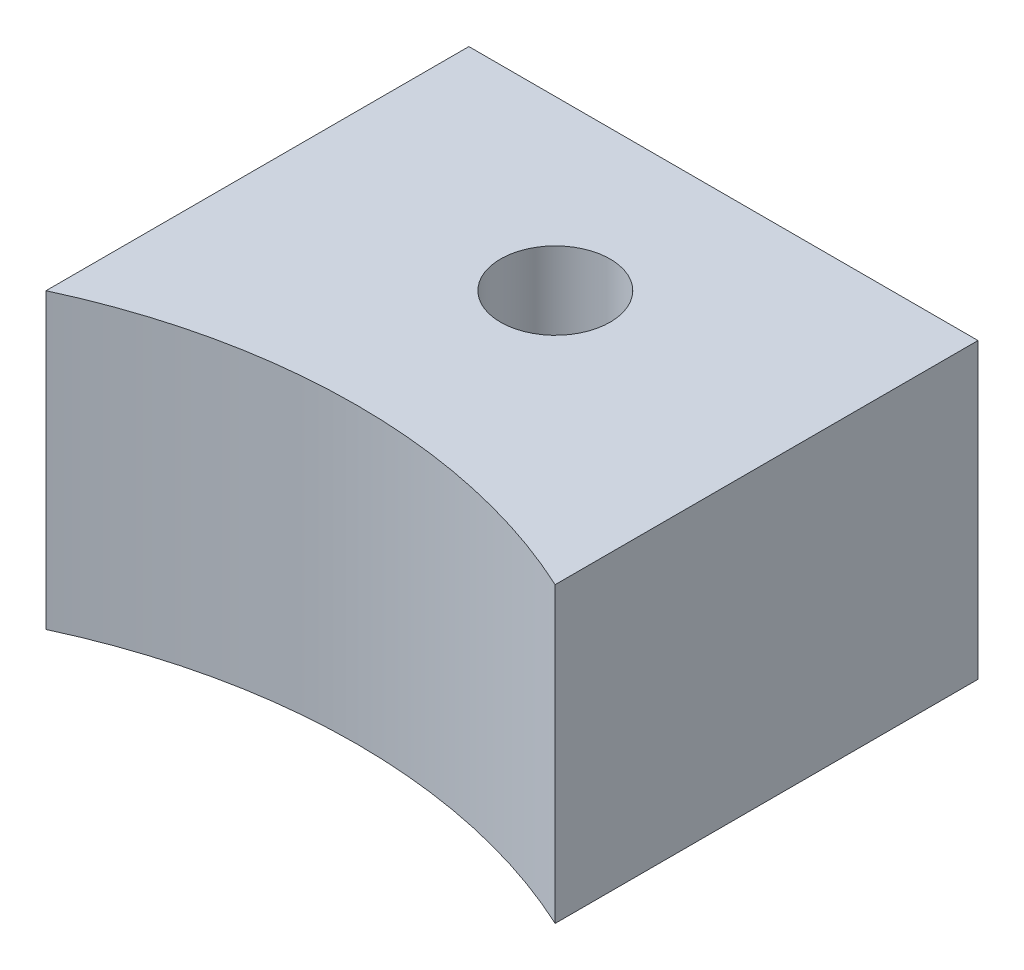
SolidWorks part; units mm, degrees
ref_plane "Plan de face" through (0, 0, 0) normal (0, 0, 1) x (1, 0, 0)
ref_plane "Plan de dessus" through (0, 0, 0) normal (0, 1, 0) x (1, 0, 0)
ref_plane "Plan de droite" through (0, 0, 0) normal (1, 0, 0) x (0, 0, -1)
sketch "Esquisse1" plane through (0, 0, 0) normal (0, 1, 0) x (1, 0, 0)
  line L0 (-14.75, 0) -> (14.75, 0)
  line L1 (14.75, 0) -> (14.75, -24.5)
  line L2 (-14.75, 0) -> (-14.75, -24.5)
  arc A0 (-14.75, -24.5) -> (14.75, -24.5) centre (0, -56.2402) cw
  circle A1 centre (0, -9.7402) radius 3.175
  point P3 (0, 0)
  dimension "D3" = 35
  dimension "D5" = 6.35
  dimension "D1" = 29.5
  dimension "D2" = 24.5
  dimension "D4" = 46.5
extrude "Boss.-Extru.1" add sketch "Esquisse1" along normal blind 17
